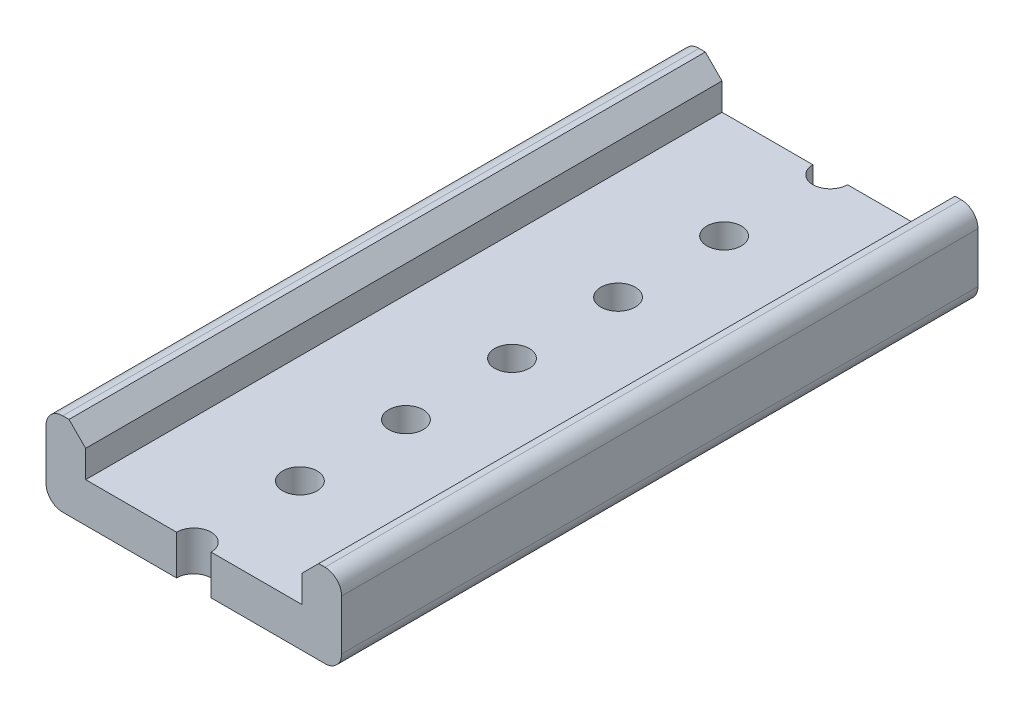
SolidWorks part; units mm, degrees
ref_plane "Front Plane" through (0, 0, 0) normal (0, 0, 1) x (1, 0, 0)
ref_plane "Top Plane" through (0, 0, 0) normal (0, 1, 0) x (1, 0, 0)
ref_plane "Right Plane" through (0, 0, 0) normal (1, 0, 0) x (0, 0, -1)
sketch "Sketch1" plane through (0, 0, 0) normal (0, 0, 1) x (1, 0, 0)
  line L0 (-17.7, -7.7) -> (-17.7, -17.7)
  line L1 (-12.7, 12.7) -> (12.7, 12.7) construction
  line L2 (-12.7, -7.7) -> (-12.7, -12.7) construction
  line L3 (-12.7, -12.7) -> (12.7, -12.7) construction
  line L4 (12.7, -7.7) -> (12.7, -12.7) construction
  line L5 (7.7, -7.7) -> (12.7, -12.7) construction
  line L6 (-7.7, -7.7) -> (0, 0) construction
  line L7 (-17.7, -17.7) -> (17.7, -17.7)
  line L8 (17.7, -7.7) -> (17.7, -17.7)
  line L9 (-17.7, 17.7) -> (17.7, 17.7) construction
  line L10 (-17.7, -7.7) -> (-12.95, -7.7)
  line L11 (-12.95, -7.7) -> (-12.95, -12.95)
  line L12 (-12.95, -12.95) -> (12.95, -12.95)
  line L13 (12.95, -7.7) -> (12.95, -12.95)
  line L14 (-17.7, 17.7) -> (-17.7, -7.7) construction
  line L15 (-17.7, 17.7) -> (-17.7, -17.7) construction
  line L16 (-12.95, 12.7) -> (-12.95, -7.7) construction
  line L17 (-12.95, 12.7) -> (-12.95, -12.95) construction
  line L18 (-12.7, 12.7) -> (-12.7, -7.7) construction
  line L19 (-12.7, 12.7) -> (-12.7, -12.7) construction
  line L20 (-12.7, 12.7) -> (0, 0) construction
  line L21 (17.7, 17.7) -> (17.7, -7.7) construction
  line L22 (17.7, 17.7) -> (17.7, -17.7) construction
  line L23 (12.95, 12.7) -> (12.95, -7.7) construction
  line L24 (12.95, 12.7) -> (12.95, -12.95) construction
  line L25 (12.7, 12.7) -> (12.7, -7.7) construction
  line L26 (12.7, 12.7) -> (12.7, -12.7) construction
  line L27 (0, 0) -> (12.7, 12.7) construction
  line L28 (-12.7, -7.7) -> (-7.7, -7.7) construction
  line L29 (12.95, -7.7) -> (17.7, -7.7)
  line L30 (-12.7, -12.7) -> (-7.7, -7.7) construction
  line L31 (-7.7, -7.7) -> (7.7, -7.7) construction
  line L32 (0, 0) -> (7.7, -7.7) construction
  line L33 (7.7, -7.7) -> (12.7, -7.7) construction
  line L34 (-12.95, -7.7) -> (-12.7, -7.7) construction
  line L35 (12.7, -7.7) -> (12.95, -7.7) construction
  point P0 (0, 0)
  dimension "D1" = 25.4
  dimension "D2" = 25.4
  dimension "D5" = 10
  dimension "D3" = 5
  dimension "D4" = 0.25
extrude "Boss-Extrude1" add sketch "Sketch1" along normal mid plane 76.2
sketch "Sketch2" plane through (0, -12.95, 0) normal (0, 1, 0) x (1, 0, 0)
  line L0 (0, 38.1) -> (0, -38.1) construction
  line L1 (12.95, 38.1) -> (-12.95, 38.1) construction
  line L2 (12.95, -38.1) -> (-12.95, -38.1) construction
  circle A0 centre (0, 25.4) radius 2.07
  circle A1 centre (0, 12.7) radius 2.07
  circle A2 centre (0, 0) radius 2.07
  circle A3 centre (0, -12.7) radius 2.07
  circle A4 centre (0, -25.4) radius 2.07
  circle A5 centre (0, -38.1) radius 2.07
  circle A6 centre (0, 38.1) radius 2.07
  point P8 (0, 0)
  dimension "D2" = 4.14
  dimension "D1" = 12.7
  dimension "D5" = 25.4
  dimension "D3" = 6
  dimension "D4" = 2
extrude "Cut-Extrude1" cut sketch "Sketch2" against normal through all both and the other way through all
chamfer "Chamfer1" distance 2 angle 45 2 edges at (12.95, -7.7, 0) (-12.95, -7.7, 0)
fillet "Fillet1" radius 2 4 edges at (17.7, -17.7, 0) (-17.7, -17.7, 0) (-17.7, -7.7, 0) (17.7, -7.7, 0)
